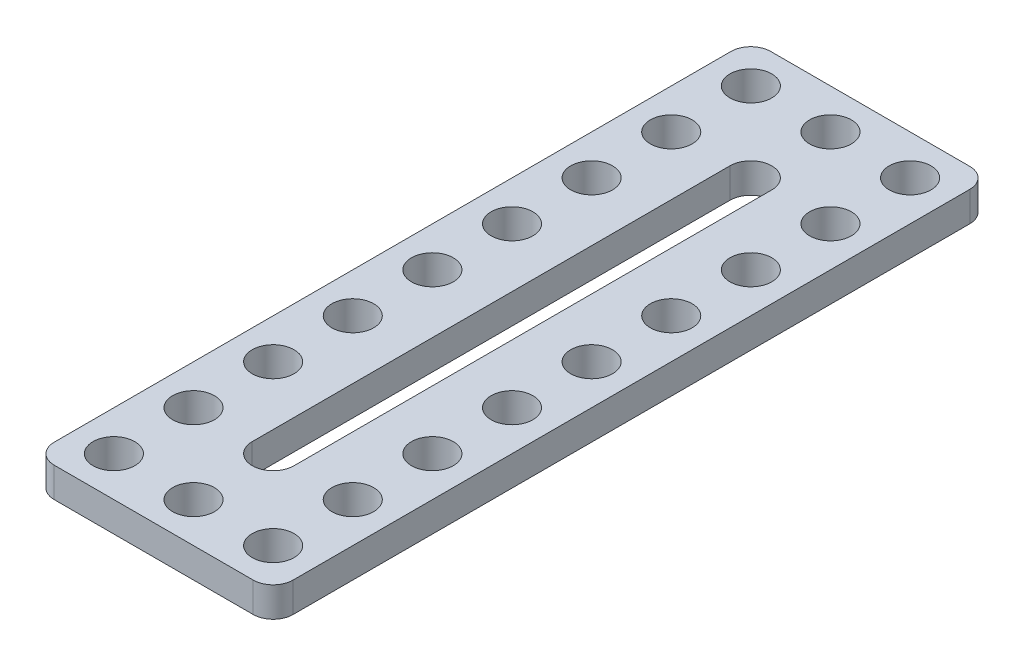
SolidWorks part; units mm, degrees
ref_plane "前视基准面" through (0, 0, 0) normal (0, 0, 1) x (1, 0, 0)
ref_plane "上视基准面" through (0, 0, 0) normal (0, 1, 0) x (1, 0, 0)
ref_plane "右视基准面" through (0, 0, 0) normal (1, 0, 0) x (0, 0, -1)
sketch "草图1" plane through (0, 0, 0) normal (0, 1, 0) x (1, 0, 0)
  line L1 (-12, 36) -> (12, 36)
  line L2 (-12, 36) -> (-12, -36)
  line L3 (-12, -36) -> (12, -36)
  line L4 (12, 36) -> (12, -36)
  line L5 (-12, 36) -> (12, -36) construction
  line L6 (-12, -36) -> (12, 36) construction
  point P0 (0, 0)
  dimension "D1" = 72
  dimension "D2" = 24
extrude "凸台-拉伸2" add sketch "草图1" along normal blind 3
sketch "草图2" plane through (0, 3, 0) normal (0, 1, 0) x (1, 0, 0)
  line L0 (0, 36) -> (0, -36) construction
  line L1 (12, 36) -> (-12, 36) construction
  line L2 (-12, -36) -> (12, -36) construction
  line L3 (-12, 36) -> (-12, -36) construction
  line L4 (-12, 0) -> (12, 0) construction
  line L5 (12, -36) -> (12, 36) construction
  circle A0 centre (-8, -32) radius 2.1
  circle A1 centre (-8, -24) radius 2.1
  circle A2 centre (-8, -16) radius 2.1
  circle A3 centre (-8, -8) radius 2.1
  circle A4 centre (-8, 0) radius 2.1
  circle A5 centre (-8, 8) radius 2.1
  circle A6 centre (-8, 16) radius 2.1
  circle A7 centre (-8, 24) radius 2.1
  circle A8 centre (-8, 32) radius 2.1
  circle A9 centre (8, -24) radius 2.1
  circle A10 centre (8, -16) radius 2.1
  circle A11 centre (8, -8) radius 2.1
  circle A12 centre (8, 0) radius 2.1
  circle A13 centre (8, 8) radius 2.1
  circle A14 centre (8, 16) radius 2.1
  circle A15 centre (8, 24) radius 2.1
  circle A16 centre (8, 32) radius 2.1
  circle A17 centre (8, -32) radius 2.1
  circle A18 centre (0, -32) radius 2.1
  circle A19 centre (0, 32) radius 2.1
  dimension "D1" = 4.2
  dimension "D2" = 4
  dimension "D3" = 4
  dimension "D6" = 8
  dimension "D4" = 9
  dimension "D5" = 2
extrude "切除-拉伸1" cut sketch "草图2" against normal blind 3
sketch "草图3" plane through (0, 3, 0) normal (0, 1, 0) x (1, 0, 0)
  line L0 (-8, -24) -> (8, -24) construction
  line L1 (-8, 24) -> (8, 24) construction
  line L2 (-12, 0) -> (12, 0) construction
  line L3 (-12, 36) -> (-12, -36) construction
  line L4 (12, -36) -> (12, 36) construction
  line L5 (-2.1, -24) -> (-2.1, 24)
  line L6 (2.1, -24) -> (2.1, 24)
  arc A0 (-2.1, -24) -> (2.1, -24) centre (0, -24) ccw
  arc A1 (-2.1, 24) -> (2.1, 24) centre (0, 24) cw
  point P19 (2.1, 0)
  point P21 (-2.1, 0)
  dimension "D1" = 4.2
extrude "切除-拉伸2" cut sketch "草图3" against normal blind 3
fillet "圆角1" radius 2 4 edges at (12, 1.5, 36) (-12, 1.5, 36) (12, 1.5, -36) (-12, 1.5, -36)
